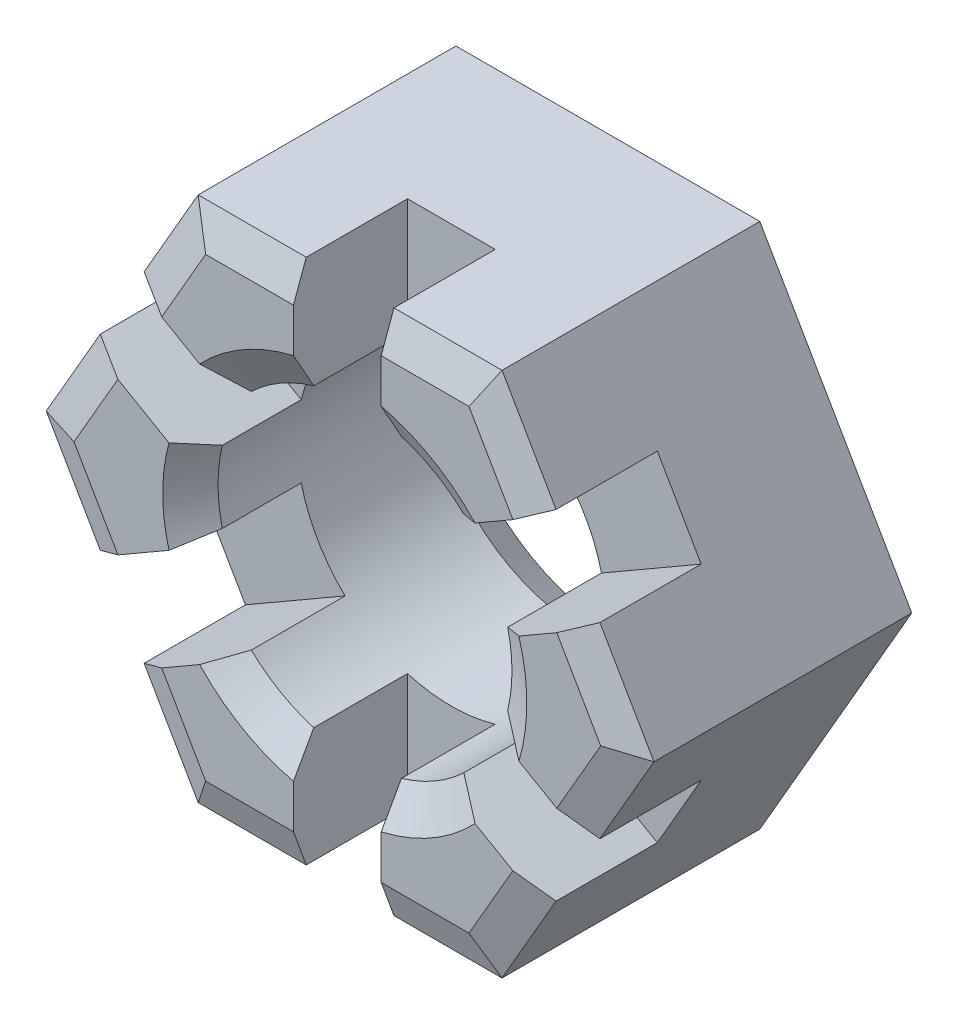
SolidWorks part; units mm, degrees
ref_plane "Plano frontal" through (0, 0, 0) normal (0, 0, 1) x (1, 0, 0)
ref_plane "Plano superior" through (0, 0, 0) normal (0, 1, 0) x (1, 0, 0)
ref_plane "Plano direito" through (0, 0, 0) normal (1, 0, 0) x (0, 0, -1)
sketch "Esboço1" plane through (0, 0, 0) normal (0, 0, 1) x (1, 0, 0)
  line L1 (17.3205, 0) -> (8.6603, 15)
  line L2 (8.6603, 15) -> (-8.6603, 15)
  line L3 (-8.6603, 15) -> (-17.3205, 0)
  line L4 (-17.3205, 0) -> (-8.6603, -15)
  line L5 (-8.6603, -15) -> (8.6603, -15)
  line L6 (8.6603, -15) -> (17.3205, 0)
  circle A0 centre (0, 0) radius 15 construction
  dimension "D1" = 30
extrude "Ressalto-extrusão1" add sketch "Esboço1" along normal blind 16
chamfer "Chanfro1" distance 2 angle 20 6 edges at (0, -15, 16) (12.9904, -7.5, 16) (12.9904, 7.5, 16) (0, 15, 16) (-12.9904, 7.5, 16) (-12.9904, -7.5, 16)
sketch "Esboço2" plane through (0, 0, 16) normal (0, 0, 1) x (1, 0, 0)
  line L0 (-17.3205, 0) -> (17.3205, 0) construction
  line L1 (-8.6603, 15) -> (-17.3205, 0) construction
  circle A0 centre (0, 0) radius 8.8
  dimension "D1" = 17.6
extrude "Corte-extrusão1" cut sketch "Esboço2" against normal blind 16
sketch "Esboço3" plane through (0, 0, 16) normal (0, 0, 1) x (1, 0, 0)
  line L0 (0, 0) -> (0, 8.8) construction
  line L1 (13.3539, 10.5966) -> (15.8539, 6.2665)
  line L2 (-2.5, 16.8631) -> (2.5, 16.8631)
  line L3 (-2.5, 16.8631) -> (-2.5, 6.8631)
  line L4 (-2.5, 6.8631) -> (2.5, 6.8631)
  line L5 (2.5, 16.8631) -> (2.5, 6.8631)
  line L6 (-2.5, 16.8631) -> (2.5, 6.8631) construction
  line L7 (-2.5, 6.8631) -> (2.5, 16.8631) construction
  line L8 (13.3539, 10.5966) -> (4.6936, 5.5966)
  line L9 (4.6936, 5.5966) -> (7.1936, 1.2665)
  line L10 (15.8539, 6.2665) -> (7.1936, 1.2665)
  line L11 (13.3539, 10.5966) -> (7.1936, 1.2665) construction
  line L12 (4.6936, 5.5966) -> (15.8539, 6.2665) construction
  line L13 (15.8539, -6.2665) -> (13.3539, -10.5966)
  line L14 (15.8539, -6.2665) -> (7.1936, -1.2665)
  line L15 (7.1936, -1.2665) -> (4.6936, -5.5966)
  line L16 (13.3539, -10.5966) -> (4.6936, -5.5966)
  line L17 (15.8539, -6.2665) -> (4.6936, -5.5966) construction
  line L18 (7.1936, -1.2665) -> (13.3539, -10.5966) construction
  line L19 (2.5, -16.8631) -> (-2.5, -16.8631)
  line L20 (2.5, -16.8631) -> (2.5, -6.8631)
  line L21 (2.5, -6.8631) -> (-2.5, -6.8631)
  line L22 (-2.5, -16.8631) -> (-2.5, -6.8631)
  line L23 (2.5, -16.8631) -> (-2.5, -6.8631) construction
  line L24 (2.5, -6.8631) -> (-2.5, -16.8631) construction
  line L25 (-13.3539, -10.5966) -> (-15.8539, -6.2665)
  line L26 (-13.3539, -10.5966) -> (-4.6936, -5.5966)
  line L27 (-4.6936, -5.5966) -> (-7.1936, -1.2665)
  line L28 (-15.8539, -6.2665) -> (-7.1936, -1.2665)
  line L29 (-13.3539, -10.5966) -> (-7.1936, -1.2665) construction
  line L30 (-4.6936, -5.5966) -> (-15.8539, -6.2665) construction
  line L31 (-15.8539, 6.2665) -> (-13.3539, 10.5966)
  line L32 (-15.8539, 6.2665) -> (-7.1936, 1.2665)
  line L33 (-7.1936, 1.2665) -> (-4.6936, 5.5966)
  line L34 (-13.3539, 10.5966) -> (-4.6936, 5.5966)
  line L35 (-15.8539, 6.2665) -> (-4.6936, 5.5966) construction
  line L36 (-7.1936, 1.2665) -> (-13.3539, 10.5966) construction
  circle A0 centre (0, 0) radius 8.8 construction
  point P6 (0, 11.8631)
  point P13 (10.2737, 5.9315)
  point P18 (10.2737, -5.9315)
  point P23 (0, -11.8631)
  point P28 (-10.2737, -5.9315)
  point P33 (-10.2737, 5.9315)
  point P38 (0, 0)
  dimension "D1" = 5
  dimension "D2" = 10
  dimension "D3" = 6
extrude "Corte-extrusão2" cut sketch "Esboço3" against normal blind 6.5
chamfer "Chanfro2" distance 2 angle 30 6 edges at (-8.8, 0, 16) (-4.4, -7.621, 16) (4.4, -7.621, 16) (8.8, 0, 16) (4.4, 7.621, 16) (-4.4, 7.621, 16)
chamfer "Chanfro3" distance 2 angle 30 1 edges at (8.8, 0, 0)
chamfer "Chanfro5" distance 1 angle 30 6 edges at (12.9904, -7.5, 0) (0, -15, 0) (-12.9904, -7.5, 0) (-12.9904, 7.5, 0) (0, 15, 0) (12.9904, 7.5, 0)
